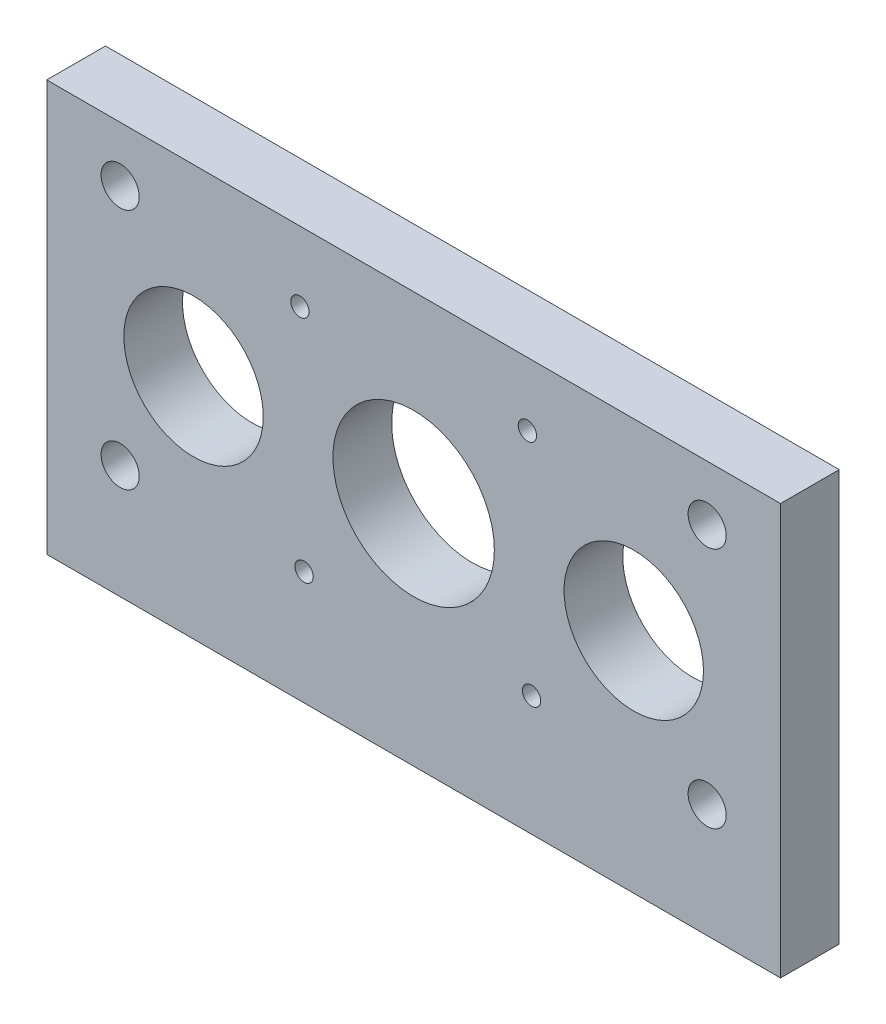
SolidWorks part; units mm, degrees
ref_plane "Ön Düzlem" through (0, 0, 0) normal (0, 0, 1) x (1, 0, 0)
ref_plane "Üst Düzlem" through (0, 0, 0) normal (0, 1, 0) x (1, 0, 0)
ref_plane "Sağ Düzlem" through (0, 0, 0) normal (1, 0, 0) x (0, 0, -1)
sketch "Çizim1" plane through (0, 0, 0) normal (0, 0, 1) x (1, 0, 0)
  line L1 (-52.0311, 28.2577) -> (47.9689, 28.2577)
  line L2 (-52.0311, 28.2577) -> (-52.0311, -27.7423)
  line L3 (-52.0311, -27.7423) -> (47.9689, -27.7423)
  line L4 (47.9689, 28.2577) -> (47.9689, -27.7423)
  circle A0 centre (-32.0311, 3.2577) radius 9.5
  circle A1 centre (27.9689, 3.2577) radius 9.5
  circle A2 centre (-2.0311, 3.2577) radius 2.0311
  dimension "D3" = 19
  dimension "19" = 19
  dimension "D4" = 20
  dimension "D5" = 20
  dimension "D6" = 25
  dimension "D7" = 25
  dimension "D8" = 25
  dimension "D1" = 100
  dimension "D2" = 56
extrude "Yükseklik-Ekstrüzyon1" add sketch "Çizim1" along normal blind 8
sketch "Çizim2" plane through (0, 0, 8) normal (0, 0, 1) x (1, 0, 0)
  circle A0 centre (-2.0311, 3.2577) radius 11
  dimension "D1" = 22
extrude "Kes-Ekstrüzyon1" cut sketch "Çizim2" against normal blind 10
sketch "Çizim3" plane through (0, 0, 0) normal (0, 0, -1) x (-1, 0, 0)
  circle A0 centre (-13.4689, 19.6174) radius 1.25
  circle A1 centre (17.5311, 18.7577) radius 1.25
  circle A2 centre (16.9624, -12.2423) radius 1.25
  circle A3 centre (-14.0376, -11.3826) radius 1.25
extrude "Kes-Ekstrüzyon2" cut sketch "Çizim3" against normal blind 10
sketch "Çizim4" plane through (0, 0, 8) normal (0, 0, 1) x (1, 0, 0)
  line L0 (-52.0311, 28.2577) -> (-52.0311, -27.7423) construction
  line L1 (47.9689, 28.2577) -> (-52.0311, 28.2577) construction
  line L2 (47.9689, -27.7423) -> (47.9689, 28.2577) construction
  line L3 (-52.0311, -27.7423) -> (47.9689, -27.7423) construction
  circle A0 centre (-42.0311, 20.7577) radius 1.619
  circle A1 centre (37.9689, 20.7577) radius 1.9761
  circle A2 centre (-42.0311, -12.2423) radius 1.8503
  circle A3 centre (37.9689, -12.2423) radius 1.4481
  dimension "D1" = 7.5
  dimension "D2" = 10
  dimension "D3" = 3.9522
  dimension "D4" = 15.5
  dimension "D5" = 10
  dimension "D6" = 15.5
  dimension "10" = 10
  dimension "7" = 7.5
  dimension "D7" = 10
hole_wizard "M5 Helisarmal için Zıvana matkabı1" positions "3B Çizim1" profile "Çizim5" hole size "M5x0.8" standard "ANSI Metric" end condition up to next
sketch3d "3B Çizim1"
  point P0 (-42.0311, 20.7577, 8)
  point P3 (37.9689, 20.7577, 8)
  point P6 (37.9689, -12.2423, 8)
  point P9 (-42.0311, -12.2423, 8)
sketch "Çizim5" plane through (-42.0311, 20.7577, 8) normal (1, 0, 0) x (0, -1, 0)
  line L0 (0, 0) -> (0, 8)
  line L1 (0, 8) -> (2.6, 8)
  line L2 (2.6, 8) -> (2.6, 0)
  line L5 (2.6, 0) -> (0, 0)
  line L11 (0, -6.35) -> (0, 107.95) construction
  dimension "Thru Hole Dia." = 5.2
  dimension "Thru Hole Depth" = 8
